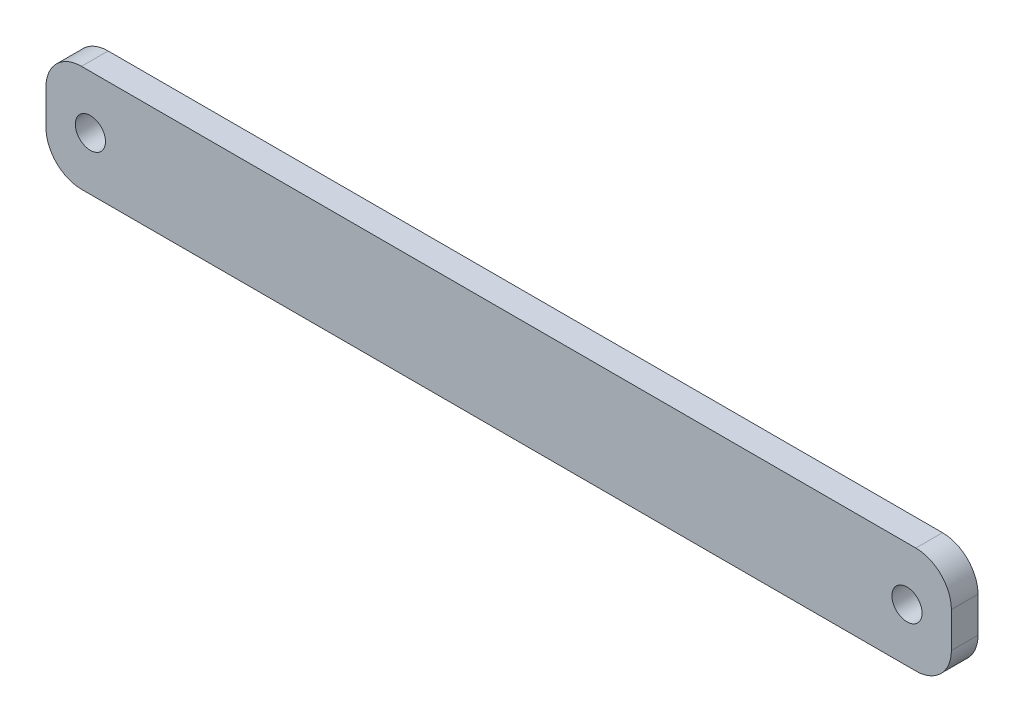
SolidWorks part; units mm, degrees
material "ABS"
ref_plane "Front Plane" through (0, 0, 0) normal (0, 0, 1) x (1, 0, 0)
ref_plane "Top Plane" through (0, 0, 0) normal (0, 1, 0) x (1, 0, 0)
ref_plane "Right Plane" through (0, 0, 0) normal (1, 0, 0) x (0, 0, -1)
sketch "Sketch1" plane through (0, 0, 0) normal (0, 0, 1) x (1, 0, 0)
  line L0 (-47, -6) -> (47, -6)
  line L1 (51, -2) -> (51, 2)
  line L2 (47, 6) -> (-47, 6)
  line L3 (-51, 2) -> (-51, -2)
  arc A0 (47, -6) -> (51, -2) centre (47, -2) ccw
  arc A1 (51, 2) -> (47, 6) centre (47, 2) ccw
  arc A2 (-47, 6) -> (-51, 2) centre (-47, 2) ccw
  arc A3 (-51, -2) -> (-47, -6) centre (-47, -2) ccw
extrude "Boss-Extrude1" add sketch "Sketch1" along normal blind 3
sketch "Sketch2" plane through (0, 0, 3) normal (0, 0, 1) x (1, 0, 0)
  circle A0 centre (-46, 0) radius 1.7
  circle A1 centre (46, 0) radius 1.7
extrude "Cut-Extrude1" cut sketch "Sketch2" against normal through all
